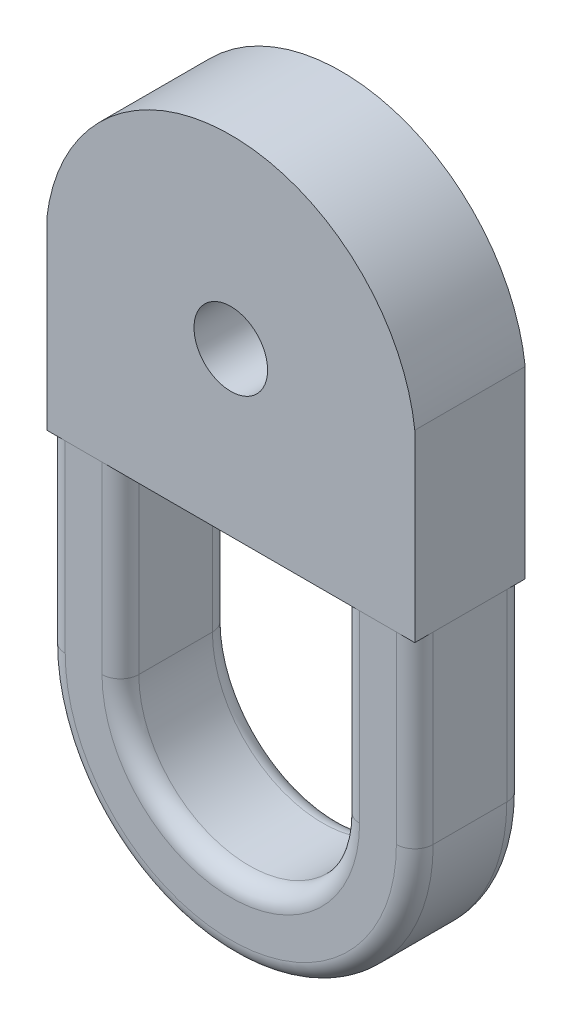
SolidWorks part; units mm, degrees
material "1060 Alloy"
ref_plane "Front Plane" through (0, 0, 0) normal (0, 0, 1) x (1, 0, 0)
ref_plane "Top Plane" through (0, 0, 0) normal (0, 1, 0) x (1, 0, 0)
ref_plane "Right Plane" through (0, 0, 0) normal (1, 0, 0) x (0, 0, -1)
sketch "Sketch1" plane through (0, 0, 0) normal (0, 0, 1) x (1, 0, 0)
  line L0 (0, 0) -> (0, 5)
  line L1 (5, 9.4479) -> (5, -31.1921) construction
  line L2 (10, 5) -> (10, 0)
  line L3 (10, 0) -> (0, 0)
  arc A0 (0, 5) -> (10, 5) centre (5, 4.4137) cw
  circle A1 centre (5, 4.4137) radius 1
  dimension "D2" = 2
  dimension "D1" = 40.64
  dimension "D3" = 10
  dimension "D4" = 5
  dimension "D5" = 0
extrude "Boss-Extrude1" add sketch "Sketch1" along normal blind 3
sketch "Sketch2" plane through (0, 0, 3) normal (0, 0, 1) x (1, 0, 0)
  line L0 (0, 0) -> (10, 0)
  line L1 (0, 0) -> (0, -5)
  line L2 (10, 0) -> (10, -5)
  line L3 (2, -5) -> (2, 0)
  line L4 (8, -5) -> (8, 0)
  line L5 (10, 0) -> (10, 5) construction
  circle A0 centre (5, -5) radius 5
  circle A1 centre (5, -5) radius 3
  line M9 (0, 0) -> (10, 0)
  dimension "D1" = 2
  dimension "D3" = 2
  dimension "D2" = 2
  dimension "D4" = 0
extrude "Boss-Extrude2" add sketch "Sketch2" against normal blind 3 separate body contours A1 L3 A0 L4 | A0 L3 L1 M9 | A0 L2 L4 M9
fillet "Fillet7" radius 0.5 12 edges at (8, -2.5, 0) (5, -8, 0) (8, -2.5, 3) (5, -8, 3) (0, -2.5, 0) (10, -2.5, 0) (10, -2.5, 3) (5, -10, 3) (2, -2.5, 0) (2, -2.5, 3) (5, -10, 0) (0, -2.5, 3)
